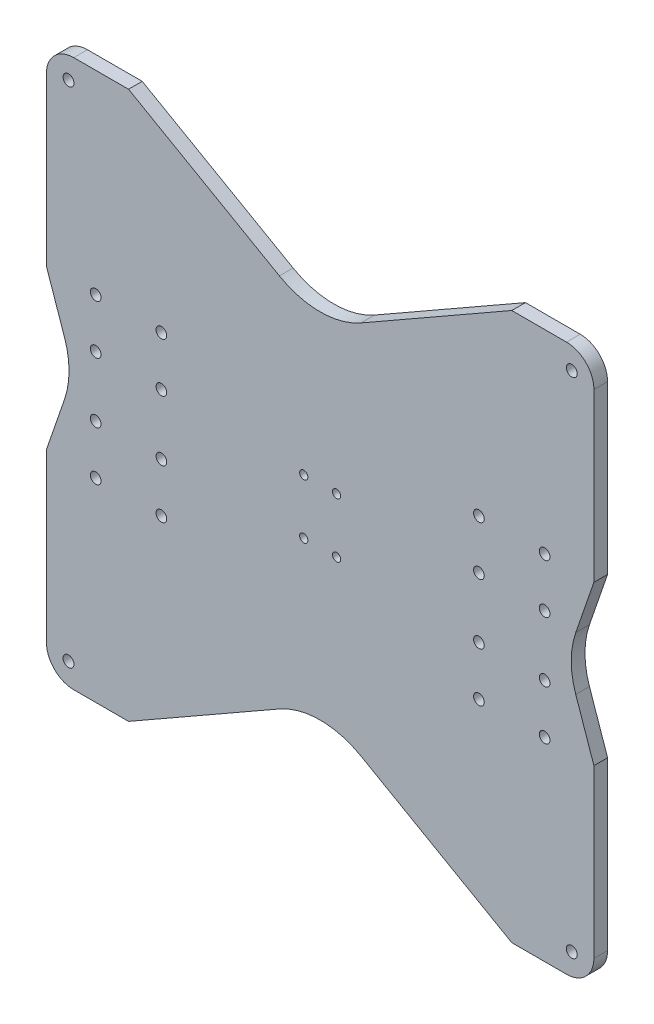
SolidWorks part; units mm, degrees
ref_plane "Front Plane" through (0, 0, 0) normal (0, 0, 1) x (1, 0, 0)
ref_plane "Top Plane" through (0, 0, 0) normal (0, 1, 0) x (1, 0, 0)
ref_plane "Right Plane" through (0, 0, 0) normal (1, 0, 0) x (0, 0, -1)
sketch "Sketch1" plane through (0, 0, 0) normal (0, 0, 1) x (1, 0, 0)
  line L0 (70, 132.7498) -> (70, -162.6372) construction
  line L1 (-90, 100) -> (-70, 100)
  line L2 (-100, 90) -> (-100, 29)
  line L3 (-90, -100) -> (-70, -100)
  line L4 (100, 90) -> (100, 29)
  line L5 (-100, 100) -> (100, -100) construction
  line L6 (-100, -100) -> (100, 100) construction
  line L7 (-70, 132.7498) -> (-70, -162.6372) construction
  line L8 (-121.9294, 0) -> (115.6873, 0) construction
  line L9 (-121.9294, 11) -> (127.292, 11) construction
  line L10 (-121.9294, -11) -> (111.2538, -11) construction
  line L11 (-58, 132.7498) -> (-58, -116.9522) construction
  line L12 (-82, 132.7498) -> (-82, -116.9522) construction
  line L13 (58, 116.0085) -> (58, -131.4445) construction
  line L14 (82, 116.0085) -> (82, -131.4445) construction
  line L15 (-121.9294, 29) -> (123.5119, 29) construction
  line L16 (-121.9294, -29) -> (123.5119, -29) construction
  line L17 (0, 85.0352) -> (0, -90) construction
  line L18 (6, 85.0352) -> (6, 65.1587) construction
  line L19 (-6, 85.0352) -> (-6, 65.1587) construction
  line L20 (-15.2579, 10) -> (13.899, 10) construction
  line L21 (-15.2579, -10) -> (14.5048, -10) construction
  line L22 (70, 100) -> (14.8842, 68.5052)
  line L23 (-14.8842, 68.5052) -> (-70, 100)
  line L24 (6, 29) -> (6, -90) construction
  line L25 (-6, 29) -> (-6, -90) construction
  line L26 (70, 100) -> (90, 100)
  line L27 (70, -100) -> (14.8842, -68.5052)
  line L28 (-14.8842, -68.5052) -> (-70, -100)
  line L29 (70, -100) -> (90, -100)
  line L30 (100, 29) -> (93.3723, 9.7797)
  line L31 (93.3723, -9.7797) -> (100, -29)
  line L32 (100, -29) -> (100, -90)
  line L33 (-100, 29) -> (-93.3723, 9.7797)
  line L34 (-93.3723, -9.7797) -> (-100, -29)
  line L35 (-100, -29) -> (-100, -90)
  circle A0 centre (-91.9239, 91.9239) radius 2
  circle A1 centre (91.9239, 91.9239) radius 2
  circle A2 centre (91.9239, -91.9239) radius 2
  circle A3 centre (-91.9239, -91.9239) radius 2
  arc A4 (100, 90) -> (90, 100) centre (90, 90) ccw
  arc A5 (90, -100) -> (100, -90) centre (90, -90) ccw
  arc A6 (-100, -90) -> (-90, -100) centre (-90, -90) ccw
  arc A7 (-100, 90) -> (-90, 100) centre (-90, 90) cw
  circle A8 centre (58, 29) radius 1.95
  circle A9 centre (82, 29) radius 1.95
  circle A10 centre (58, 11) radius 1.95
  circle A11 centre (82, 11) radius 1.95
  circle A12 centre (58, -11) radius 1.95
  circle A13 centre (58, -29) radius 1.95
  circle A14 centre (82, -11) radius 1.95
  circle A15 centre (82, -29) radius 1.95
  circle A16 centre (-82, 29) radius 1.95
  circle A17 centre (-58, 29) radius 1.95
  circle A18 centre (-82, 11) radius 1.95
  circle A19 centre (-58, 11) radius 1.95
  circle A20 centre (-82, -11) radius 1.95
  circle A21 centre (-82, -29) radius 1.95
  circle A22 centre (-58, -11) radius 1.95
  circle A23 centre (-58, -29) radius 1.95
  circle A24 centre (-6, 10) radius 1.5
  circle A25 centre (6, 10) radius 1.5
  circle A26 centre (-6, -10) radius 1.5
  circle A27 centre (6, -10) radius 1.5
  arc A28 (14.8842, 68.5052) -> (-14.8842, 68.5052) centre (0, 94.5525) cw
  arc A29 (14.8842, -68.5052) -> (-14.8842, -68.5052) centre (0, -94.5525) ccw
  arc A30 (93.3723, -9.7797) -> (93.3723, 9.7797) centre (121.7335, 0) cw
  arc A31 (-93.3723, -9.7797) -> (-93.3723, 9.7797) centre (-121.7335, 0) ccw
  point P0 (0, 0)
  point P103 (0, 60)
  point P118 (90, 0)
  dimension "D2" = 4
  dimension "D3" = 130
  dimension "D4" = 130
  dimension "D7" = 10
  dimension "D18" = 3.9
  dimension "D23" = 3
  dimension "D25" = 30
  dimension "D27" = 30
  dimension "D1" = 200
  dimension "D5" = 130
  dimension "D6" = 130
  dimension "D8" = 140
  dimension "D9" = 70
  dimension "D10" = 11
  dimension "D11" = 11
  dimension "D12" = 12
  dimension "D13" = 12
  dimension "D14" = 12
  dimension "D15" = 12
  dimension "D16" = 18
  dimension "D17" = 18
  dimension "D19" = 6
  dimension "D20" = 6
  dimension "D21" = 10
  dimension "D22" = 10
  dimension "D24" = 40
  dimension "D26" = 10
extrude "Boss-Extrude1" add sketch "Sketch1" along normal blind 5
